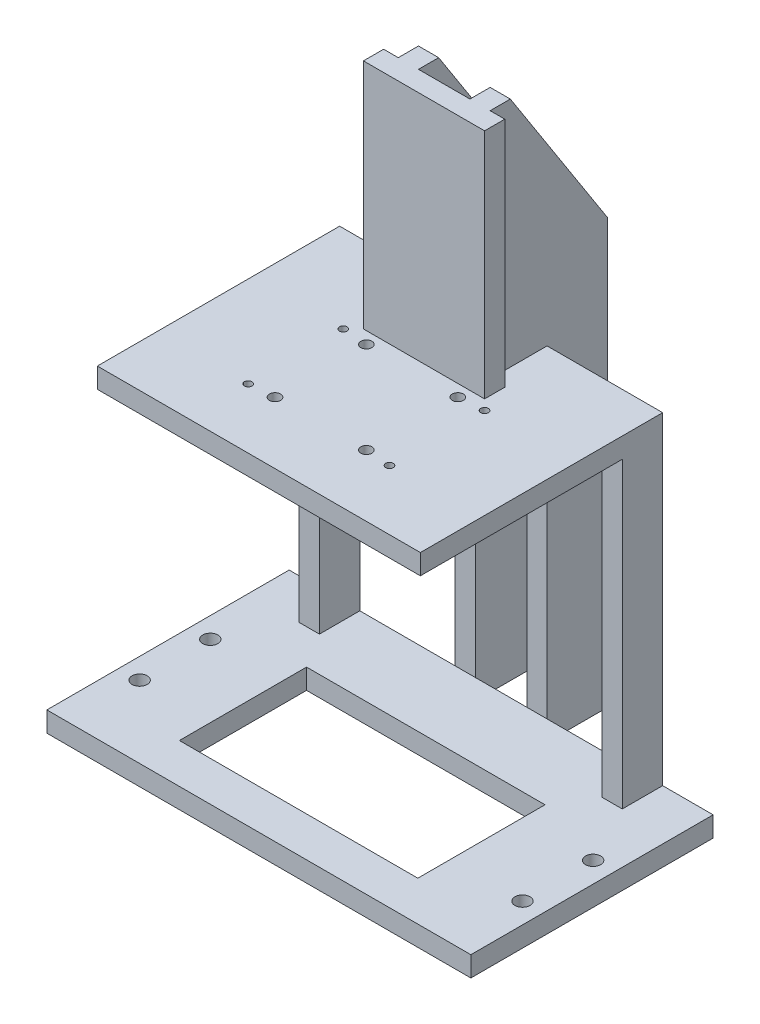
SolidWorks part; units mm, degrees
ref_plane "Front Plane" through (0, 0, 0) normal (0, 0, 1) x (1, 0, 0)
ref_plane "Top Plane" through (0, 0, 0) normal (0, 1, 0) x (1, 0, 0)
ref_plane "Right Plane" through (0, 0, 0) normal (1, 0, 0) x (0, 0, -1)
sketch "Sketch1" plane through (0, 0, 0) normal (0, 0, 1) x (1, 0, 0)
  line L0 (-203.2, 215.9) -> (-203.2, -215.9)
  line L1 (-177.8, 190.5) -> (177.8, 190.5)
  line L2 (-177.8, 190.5) -> (-177.8, -190.5)
  line L3 (-177.8, -190.5) -> (177.8, -190.5)
  line L4 (177.8, 190.5) -> (177.8, -190.5)
  line L5 (-177.8, 190.5) -> (177.8, -190.5) construction
  line L6 (-177.8, -190.5) -> (177.8, 190.5) construction
  line L7 (-203.2, -215.9) -> (203.2, -215.9)
  line L8 (203.2, 215.9) -> (203.2, -215.9)
  line L9 (-203.2, 215.9) -> (203.2, 215.9)
  point P0 (0, 0)
  dimension "D1" = 381
  dimension "D2" = 355.6
  dimension "D3" = 25.4
extrude "Boss-Extrude1" add sketch "Sketch1" along normal blind 304.8
sketch "Sketch2" plane through (203.2, 0, 0) normal (1, 0, 0) x (0, 0, -1)
  line L0 (-304.8, 190.5) -> (0, 190.5) construction
  line L1 (-304.8, 190.5) -> (-50.8, 190.5)
  line L2 (-304.8, 190.5) -> (-304.8, -190.5)
  line L3 (-304.8, -190.5) -> (-50.8, -190.5)
  line L4 (-50.8, 190.5) -> (-50.8, -190.5)
  line L5 (-304.8, -190.5) -> (0, -190.5) construction
  line L7 (0, -215.9) -> (0, 215.9) construction
  line L8 (-304.8, -215.9) -> (-304.8, 215.9) construction
  dimension "D2" = 50.8
extrude "Cut-Extrude1" cut sketch "Sketch2" against normal through all
sketch "Sketch3" plane through (0, 215.9, 0) normal (0, 1, 0) x (1, 0, 0)
  line L0 (203.2, 0) -> (-203.2, 0) construction
  line L1 (-57.785, 0) -> (-32.385, 0)
  line L2 (-57.785, 0) -> (-57.785, -97.028)
  line L3 (-57.785, -97.028) -> (-32.385, -97.028)
  line L4 (-32.385, 0) -> (-32.385, -71.628)
  line L5 (0, 0) -> (0, -71.628) construction
  line L6 (32.385, 0) -> (57.785, 0)
  line L7 (32.385, 0) -> (32.385, -71.628)
  line L8 (32.385, -97.028) -> (57.785, -97.028)
  line L9 (57.785, 0) -> (57.785, -97.028)
  line L10 (-32.385, -71.628) -> (32.385, -71.628)
  line L11 (-32.385, -97.028) -> (32.385, -97.028)
  line L12 (0, -97.028) -> (0, -159.6325) construction
  line L13 (-203.2, -304.8) -> (-203.2, 0) construction
  dimension "D1" = 97.028
  dimension "D2" = 25.4
  dimension "D3" = 25.4
  dimension "D4" = 71.628
  dimension "D5" = 25.4
  dimension "D6" = 25.4
  dimension "D7" = 203.2
  dimension "D8" = 25.4
  dimension "D9" = 64.77
  dimension "D10" = 32.385
extrude "Boss-Extrude2" add sketch "Sketch3" along normal blind 101.6
sketch "Sketch4" plane through (0, -215.9, 0) normal (0, -1, 0) x (1, 0, 0)
  line L0 (0, 304.8) -> (0, 55.2685) construction
  line L1 (-57.785, 0) -> (-32.385, 0)
  line L4 (-32.385, 0) -> (-32.385, -76.2)
  line L5 (32.385, 0) -> (57.785, 0)
  line L6 (32.385, 0) -> (32.385, -76.2)
  line L7 (32.385, -76.2) -> (57.785, -76.2)
  line L8 (57.785, 0) -> (57.785, -76.2)
  line L9 (-203.2, 304.8) -> (203.2, 304.8) construction
  line L10 (-32.385, -76.2) -> (32.385, -76.2) construction
  line L11 (0, -76.2) -> (0, -39.0434) construction
  line L12 (-32.385, -76.2) -> (-57.785, -76.2)
  line L13 (-57.785, -76.2) -> (-57.785, 0)
  dimension "D1" = 25.4
  dimension "D2" = 76.2
  dimension "D3" = 64.77
  dimension "D4" = 25.4
extrude "Boss-Extrude3" add sketch "Sketch4" against normal up to surface (533.4 mm away) up to face at (0, 317.5, 42.164)
sketch "Sketch5" plane through (-57.785, 0, 0) normal (-1, 0, 0) x (0, 0, 1)
  line L0 (-76.2, 317.5) -> (46.228, 508)
  line L1 (97.028, 317.5) -> (97.028, 508)
  line L2 (97.028, 508) -> (46.228, 508)
  line L3 (-76.2, 317.5) -> (97.028, 317.5) construction
  line L4 (-76.2, 317.5) -> (97.028, 317.5)
  dimension "D1" = 190.5
  dimension "D2" = 50.8
extrude "Boss-Extrude4" add sketch "Sketch5" against normal up to surface (25.4 mm away) up to face at (-32.385, 79.375, -1.143)
sketch "Sketch6" plane through (57.785, 0, 0) normal (1, 0, 0) x (0, 0, -1)
  line L0 (-71.628, 317.5) -> (76.2, 317.5)
  line L5 (0, 215.9) -> (0, 190.5)
  line L6 (0, 190.5) -> (0, -190.5)
  line L7 (0, -190.5) -> (0, -215.9)
  line L11 (-71.628, 215.9) -> (0, 215.9)
  line L16 (0, -215.9) -> (76.2, -215.9)
  line L17 (76.2, 317.5) -> (-46.228, 508)
  line L18 (76.2, 317.5) -> (-46.228, 508)
  line L19 (-46.228, 508) -> (-97.028, 508)
  line L20 (-46.228, 508) -> (-97.028, 508)
  line L21 (-71.628, 317.5) -> (-71.628, 215.9)
  line L32 (-97.028, 508) -> (-97.028, 317.5)
  line L33 (-97.028, 508) -> (-97.028, 317.5)
  line L34 (-97.028, 317.5) -> (-71.628, 317.5)
  line L35 (-97.028, 317.5) -> (-71.628, 317.5)
  line L36 (76.2, -215.9) -> (76.2, 317.5)
  line L37 (76.2, -215.9) -> (76.2, 317.5)
  line M18 (76.2, 317.5) -> (-97.028, 317.5)
  dimension "D1" = 0
extrude "Boss-Extrude5" add sketch "Sketch6" against normal up to surface (25.4 mm away) contours L20 L33 L18 M18 up to face at (32.385, 79.375, -1.143)
sketch "Sketch7" plane through (0, 508, 0) normal (0, 1, 0) x (1, 0, 0)
  line L0 (0, -71.628) -> (0, -97.028) construction
  line L1 (32.385, -71.628) -> (-32.385, -71.628) construction
  line L2 (-32.385, -97.028) -> (32.385, -97.028) construction
  line L4 (-76.2, -71.628) -> (76.2, -71.628)
  line L5 (-76.2, -71.628) -> (-76.2, -97.028)
  line L6 (-76.2, -97.028) -> (76.2, -97.028)
  line L7 (76.2, -71.628) -> (76.2, -97.028)
  line L8 (-76.2, -71.628) -> (76.2, -97.028) construction
  line L9 (-76.2, -97.028) -> (76.2, -71.628) construction
  point P6 (0, -84.328)
  dimension "D1" = 152.4
extrude "Boss-Extrude6" add sketch "Sketch7" against normal up to surface (292.1 mm away) up to face at (0, 215.9, 100.457)
sketch "Sketch8" plane through (0, 215.9, 0) normal (0, 1, 0) x (1, 0, 0)
  line L0 (76.2, -97.028) -> (-76.2, -97.028) construction
  line L1 (-203.2, -152.4) -> (0, -152.4) construction
  line L2 (-203.2, -304.8) -> (-203.2, 0) construction
  line L7 (-57.5, -112.028) -> (57.5, -112.028) construction
  circle A0 centre (88.883, -229.362) radius 4.7625
  circle A1 centre (57.5, -227.028) radius 7
  circle A2 centre (-88.917, -229.362) radius 4.7625
  circle A3 centre (-57.5, -227.028) radius 7
  circle A4 centre (-88.917, -109.728) radius 4.7625
  circle A5 centre (57.5, -112.028) radius 7
  circle A6 centre (88.883, -109.728) radius 4.7625
  circle A7 centre (-57.5, -112.028) radius 7
  point P0 (0, -97.028)
  point P23 (3.81, -97.028)
  dimension "D2" = 115
  dimension "D3" = 177.8
  dimension "D5" = 119.634
  dimension "D6" = 115
  dimension "D7" = 115
  dimension "D8" = 119.634
  dimension "D1" = 115
  dimension "D4" = 177.8
  dimension "D9" = 31.417
extrude "Cut-Extrude2" cut sketch "Sketch8" against normal blind 25.4
sketch "Sketch9" plane through (0, 190.5, 0) normal (0, -1, 0) x (1, 0, 0)
  circle A0 centre (-57.5, 227.028) radius 12.7
  circle A1 centre (57.5, 227.028) radius 12.7
  circle A2 centre (57.5, 112.028) radius 12.7
  circle A3 centre (-57.5, 112.028) radius 12.7
  dimension "D1" = 25.4
  dimension "D2" = 25.4
  dimension "D3" = 25.4
  dimension "D4" = 25.4
extrude "Cut-Extrude3" cut sketch "Sketch9" against normal blind 12.7
sketch "Sketch10" plane through (57.785, 0, 0) normal (1, 0, 0) x (0, 0, -1)
  line L0 (-71.628, 317.5) -> (76.2, 317.5)
  line L9 (-46.228, 508) -> (-71.628, 508)
  line L10 (-71.628, 508) -> (-71.628, 215.9)
  line L11 (-71.628, 215.9) -> (0, 215.9)
  line L12 (0, 215.9) -> (0, 190.5)
  line L13 (0, 190.5) -> (0, -190.5)
  line L14 (0, -190.5) -> (0, -215.9)
  line L15 (0, -215.9) -> (76.2, -215.9)
  line L16 (76.2, -215.9) -> (76.2, 317.5)
  line L17 (76.2, 317.5) -> (-46.228, 508)
  line L18 (-46.228, 508) -> (-71.628, 508)
  line L19 (-71.628, 508) -> (-71.628, 317.5)
  line L26 (76.2, 317.5) -> (-46.228, 508)
  dimension "D1" = 0
extrude "Boss-Extrude7" add sketch "Sketch10" against normal up to surface (25.4 mm away) up to face at (32.385, 148.1667, 4.1204)
sketch "Sketch11" plane through (203.2, 0, 0) normal (1, 0, 0) x (0, 0, -1)
  line L1 (-304.8, -190.5) -> (0, -190.5)
  line L2 (-304.8, -190.5) -> (-304.8, -215.9)
  line L3 (-304.8, -215.9) -> (0, -215.9)
  line L4 (0, -190.5) -> (0, -215.9)
extrude "Boss-Extrude8" add sketch "Sketch11" along normal blind 63.5
sketch "Sketch12" plane through (-203.2, 0, 0) normal (-1, 0, 0) x (0, 0, 1)
  line L1 (304.8, -190.5) -> (0, -190.5)
  line L2 (304.8, -190.5) -> (304.8, -215.9)
  line L3 (304.8, -215.9) -> (0, -215.9)
  line L4 (0, -190.5) -> (0, -215.9)
extrude "Boss-Extrude9" add sketch "Sketch12" along normal blind 63.5
sketch "Sketch13" plane through (0, -215.9, 0) normal (0, -1, 0) x (1, 0, 0)
  point P0 (266.7, 0)
  point P1 (-266.7, 0)
  point P3 (32.385, 0)
  point P5 (-32.385, 0)
sketch "Sketch14" plane through (0, -215.9, 0) normal (0, -1, 0) x (1, 0, 0)
  circle A0 centre (-240.792, 213.978) radius 9.525
  circle A1 centre (-240.792, 125.078) radius 9.525
  circle A2 centre (240.792, 213.978) radius 9.525
  circle A3 centre (240.792, 125.078) radius 9.525
  dimension "D1" = 19.05
  dimension "D2" = 19.05
  dimension "D3" = 19.05
  dimension "D4" = 19.05
extrude "Cut-Extrude4" cut sketch "Sketch14" against normal through all
sketch "Sketch15" plane through (0, -215.9, 0) normal (0, -1, 0) x (1, 0, 0)
  circle A0 centre (-240.792, 213.978) radius 9.6682
  circle A1 centre (-240.792, 125.078) radius 10.2938
  circle A2 centre (240.792, 213.978) radius 10.5109
  circle A3 centre (240.792, 125.078) radius 15.748
  dimension "D1" = 31.496
sketch "Sketch16" plane through (0, -215.9, 0) normal (0, -1, 0) x (1, 0, 0)
  line L0 (-266.7, 0) -> (-266.7, 304.8) construction
  line L1 (-150, 254.8) -> (150, 254.8)
  line L2 (-150, 254.8) -> (-150, 94.8)
  line L3 (-150, 94.8) -> (150, 94.8)
  line L4 (150, 254.8) -> (150, 94.8)
  line L5 (-266.7, 304.8) -> (266.7, 304.8) construction
  dimension "D1" = 300
  dimension "D2" = 160
  dimension "D3" = 116.7
  dimension "D4" = 50
extrude "Cut-Extrude5" cut sketch "Sketch16" against normal blind 30
